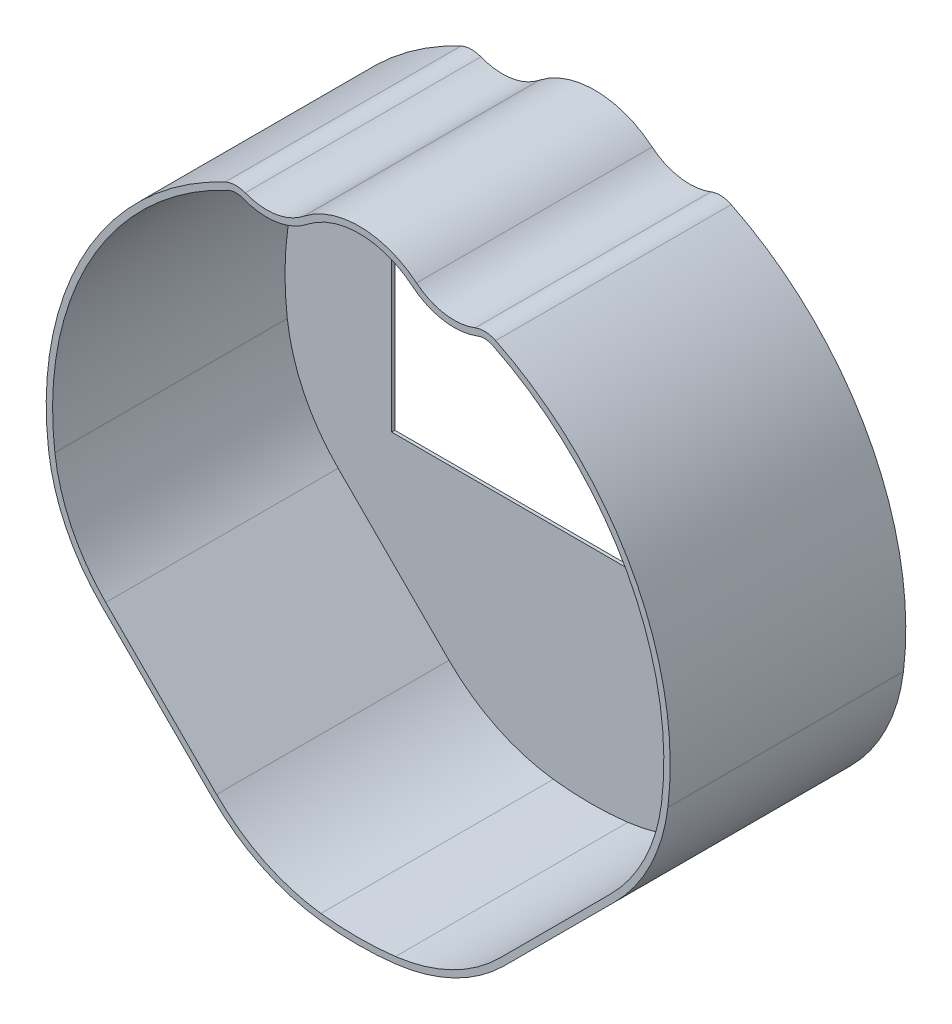
SolidWorks part; units mm, degrees
material "PE High Density"
ref_plane "Front Plane" through (0, 0, 0) normal (0, 0, 1) x (1, 0, 0)
ref_plane "Top Plane" through (0, 0, 0) normal (0, 1, 0) x (1, 0, 0)
ref_plane "Right Plane" through (0, 0, 0) normal (1, 0, 0) x (0, 0, -1)
sketch "Sketch1" plane through (0, 0, 0) normal (0, 0, 1) x (1, 0, 0)
  line L0 (40.3565, -22.9474) -> (22.9474, -40.3565)
  line L1 (-22.9474, -40.3565) -> (-40.3565, -22.9474)
  arc A0 (-17.7314, 44.4305) -> (-8.4882, 45.8998) centre (-14.3636, 53.0521) ccw
  arc A1 (-8.4882, 45.8998) -> (9.1639, 45.6208) centre (0.1631, 34.7024) cw
  arc A2 (9.1639, 45.6208) -> (18.3859, 44.1282) centre (15.0517, 52.763) ccw
  arc A3 (18.3859, 44.1282) -> (21.5891, 43.9876) centre (19.8268, 40.3968) cw
  arc A4 (21.5891, 43.9876) -> (48.6336, -5.9813) centre (0, 0) cw
  arc A5 (48.6336, -5.9813) -> (40.3565, -22.9474) centre (19.8504, -2.4413) cw
  arc A6 (22.9474, -40.3565) -> (5.9813, -48.6336) centre (2.4413, -19.8504) cw
  arc A7 (5.9813, -48.6336) -> (-5.9813, -48.6336) centre (0, 0) cw
  arc A8 (-5.9813, -48.6336) -> (-22.9474, -40.3565) centre (-2.4413, -19.8504) cw
  arc A9 (-40.3565, -22.9474) -> (-48.6336, -5.9813) centre (-19.8504, -2.4413) cw
  arc A10 (-48.6336, -5.9813) -> (-20.8923, 44.3228) centre (0, 0) cw
  arc A11 (-20.8923, 44.3228) -> (-17.7314, 44.4305) centre (-19.1868, 40.7046) cw
  dimension "D1" = 9.2561
  dimension "D2" = 14.1501
  dimension "D3" = 4
  dimension "D4" = 49
  dimension "D5" = 29
  dimension "D6" = 0.1631
  dimension "D7" = 2.4413
  dimension "D8" = 9.1639
  dimension "D9" = 18.3859
  dimension "D10" = 8.4882
  dimension "D11" = 14.3636
extrude "Boss-Extrude1" add sketch "Sketch1" along normal blind 37
sketch "Sketch3" plane through (0, 0, 37) normal (0, 0, 1) x (1, 0, 0)
  line L4 (-39.6494, -22.2403) -> (-22.2403, -39.6494)
  line L5 (22.2403, -39.6494) -> (39.6494, -22.2403)
  line L6 (-39.6494, -22.2403) -> (-22.2403, -39.6494)
  line L7 (22.2403, -39.6494) -> (39.6494, -22.2403)
  arc A24 (-18.0953, 43.499) -> (-20.4659, 43.4183) centre (-19.1868, 40.7046) ccw
  arc A25 (-20.4659, 43.4183) -> (-47.6411, -5.8592) centre (0, 0) ccw
  arc A26 (-47.6411, -5.8592) -> (-39.6494, -22.2403) centre (-19.8504, -2.4413) ccw
  arc A27 (-22.2403, -39.6494) -> (-5.8592, -47.6411) centre (-2.4413, -19.8504) ccw
  arc A28 (-5.8592, -47.6411) -> (5.8592, -47.6411) centre (0, 0) ccw
  arc A29 (5.8592, -47.6411) -> (22.2403, -39.6494) centre (2.4413, -19.8504) ccw
  arc A30 (39.6494, -22.2403) -> (47.6411, -5.8592) centre (19.8504, -2.4413) ccw
  arc A31 (47.6411, -5.8592) -> (21.1485, 43.0899) centre (0, 0) ccw
  arc A32 (21.1485, 43.0899) -> (18.7461, 43.1954) centre (19.8268, 40.3968) ccw
  arc A33 (8.5278, 44.8492) -> (18.7461, 43.1954) centre (15.0517, 52.763) ccw
  arc A34 (8.5278, 44.8492) -> (-7.8655, 45.1172) centre (0.1631, 34.7024) ccw
  arc A35 (-18.0953, 43.499) -> (-7.8655, 45.1172) centre (-14.3636, 53.0521) ccw
  arc A36 (-18.0953, 43.499) -> (-20.4659, 43.4183) centre (-19.1868, 40.7046) ccw
  arc A37 (-20.4659, 43.4183) -> (-47.6411, -5.8592) centre (0, 0) ccw
  arc A38 (-47.6411, -5.8592) -> (-39.6494, -22.2403) centre (-19.8504, -2.4413) ccw
  arc A39 (-22.2403, -39.6494) -> (-5.8592, -47.6411) centre (-2.4413, -19.8504) ccw
  arc A40 (-5.8592, -47.6411) -> (5.8592, -47.6411) centre (0, 0) ccw
  arc A41 (5.8592, -47.6411) -> (22.2403, -39.6494) centre (2.4413, -19.8504) ccw
  arc A42 (39.6494, -22.2403) -> (47.6411, -5.8592) centre (19.8504, -2.4413) ccw
  arc A43 (47.6411, -5.8592) -> (21.1485, 43.0899) centre (0, 0) ccw
  arc A44 (21.1485, 43.0899) -> (18.7461, 43.1954) centre (19.8268, 40.3968) ccw
  arc A45 (8.5278, 44.8492) -> (18.7461, 43.1954) centre (15.0517, 52.763) ccw
  arc A46 (8.5278, 44.8492) -> (-7.8655, 45.1172) centre (0.1631, 34.7024) ccw
  arc A47 (-18.0953, 43.499) -> (-7.8655, 45.1172) centre (-14.3636, 53.0521) ccw
  dimension "D1" = 1
extrude "Cut-Extrude1" cut sketch "Sketch3" against normal blind 36.5
sketch "Sketch5" plane through (0, 0, 0) normal (0, 0, -1) x (-1, 0, 0)
  line L0 (31.25, 14.8868) -> (-32.25, 14.8868) construction
  line L1 (-32.25, -13.1132) -> (31.25, -13.1132) construction
  line L2 (31.25, 14.8868) -> (-32.25, 14.8868)
  line L3 (-32.25, -13.1132) -> (31.25, -13.1132)
  line L4 (-32.25, 14.8868) -> (-32.25, -13.1132)
  line L5 (31.25, 14.8868) -> (31.25, -13.1132)
extrude "Cut-Extrude2" cut sketch "Sketch5" against normal up to next
